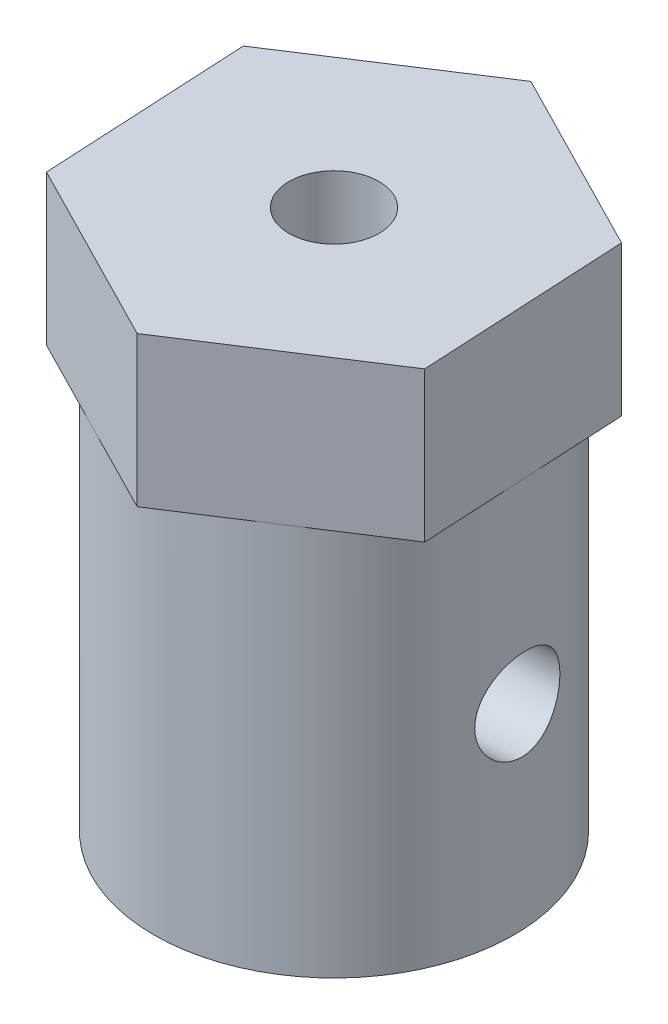
SolidWorks part; units mm, degrees
ref_plane "Alzado" through (0, 0, 0) normal (0, 0, 1) x (1, 0, 0)
ref_plane "Planta" through (0, 0, 0) normal (0, 1, 0) x (1, 0, 0)
ref_plane "Vista lateral" through (0, 0, 0) normal (1, 0, 0) x (0, 0, -1)
sketch "Croquis1" plane through (0, 0, 0) normal (0, 1, 0) x (1, 0, 0)
  circle A0 centre (0, 0) radius 6
  circle A1 centre (0, 0) radius 4
  dimension "D1" = 12
  dimension "D2" = 8
extrude "Saliente-Extruir1" add sketch "Croquis1" along normal blind 13
sketch "Croquis2" plane through (0, 13, 0) normal (0, 1, 0) x (1, 0, 0)
  line L1 (6.1711, -3.1492) -> (5.8128, 3.7697)
  line L2 (5.8128, 3.7697) -> (-0.3582, 6.9189)
  line L3 (-0.3582, 6.9189) -> (-6.1711, 3.1492)
  line L4 (-6.1711, 3.1492) -> (-5.8128, -3.7697)
  line L5 (-5.8128, -3.7697) -> (0.3582, -6.9189)
  line L6 (0.3582, -6.9189) -> (6.1711, -3.1492)
  circle A0 centre (0, 0) radius 6 construction
  circle A1 centre (0, 0) radius 1.5
  dimension "D2" = 3
  dimension "D1" = 12
extrude "Saliente-Extruir2" add sketch "Croquis2" along normal blind 5
sketch "Croquis3" plane through (-5.992, 0, 0.3103) normal (-0.9987, 0, 0.0517) x (0.0517, 0, 0.9987)
  line L6 (0, 13) -> (3.4641, 13) construction
  circle A0 centre (-0.0073, 6.5) radius 1.5
  dimension "D1" = 3
  dimension "D2" = 6.5
extrude "Cortar-Extruir1" cut sketch "Croquis3" against normal blind 24
